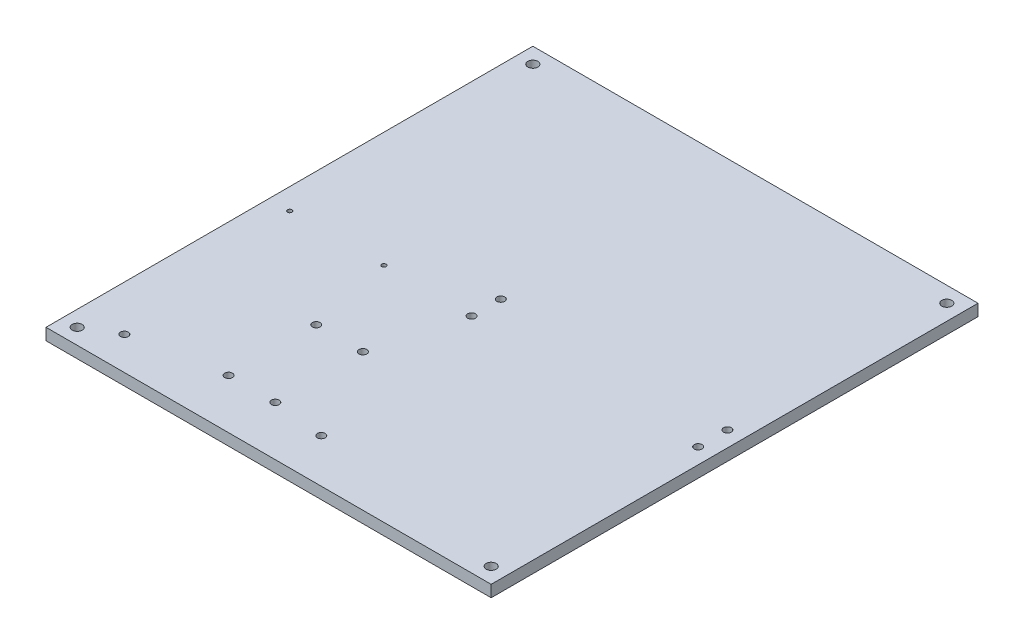
SolidWorks part; units mm, degrees
ref_plane "Front" through (0, 0, 0) normal (0, 0, 1) x (1, 0, 0)
ref_plane "Top" through (0, 0, 0) normal (0, 1, 0) x (1, 0, 0)
ref_plane "Right" through (0, 0, 0) normal (1, 0, 0) x (0, 0, -1)
sketch "Sketch1" plane through (0, 0, 0) normal (0, 1, 0) x (1, 0, 0)
  line L0 (-114.3, 125) -> (114.3, -125) construction
  line L1 (-114.3, 125) -> (114.3, 125)
  line L2 (-114.3, 125) -> (-114.3, -125)
  line L3 (-114.3, -125) -> (114.3, -125)
  line L4 (114.3, 125) -> (114.3, -125)
  dimension "D1" = 228.6
  dimension "D2" = 250
extrude "PLATE" add sketch "Sketch1" along normal mid plane 6
sketch "Sketch2" plane through (0, 3, 0) normal (0, 1, 0) x (1, 0, 0)
  line L0 (-114.3, -125) -> (114.3, -125) construction
  line L1 (114.3, -125) -> (114.3, 125) construction
  circle A0 centre (106.3, -10.7) radius 2
  circle A1 centre (106.3, 4.3) radius 2
  dimension "D1" = 114.3
  dimension "D2" = 8
  dimension "D3" = 4
  dimension "D4" = 15
extrude "MUX_BRACKET_HOLES" cut sketch "Sketch2" against normal blind 6
pattern_linear "MUX_BRACKET_PATTERN" count 2 spacing 116.35 along (-1, 0, 0) of "MUX_BRACKET_HOLES"
sketch "Sketch3" plane through (0, 3, 0) normal (0, 1, 0) x (1, 0, 0)
  circle A0 centre (-22.05, -54.5) radius 2
  circle A2 centre (-10.05, -10.7) radius 2 construction
  dimension "D1" = 10
  dimension "D2" = 4
  dimension "D3" = 43.8
extrude "PUMP_STAND_HOLE" cut sketch "Sketch3" against normal through all
pattern_linear "PUMP_STAND_PATTERN" count 2 spacing 24 along (-1, 0, 0) count 2 spacing 45 along (0, 0, 1) of "PUMP_STAND_HOLE"
sketch "Sketch4" plane through (0, 3, 0) normal (0, 1, 0) x (1, 0, 0)
  circle A0 centre (4.55, -102.5) radius 2
  circle A2 centre (-22.05, -99.5) radius 2 construction
  dimension "D1" = 26.6
  dimension "D2" = 3
  dimension "D3" = 4
extrude "PUMP_INPUT_STAND_HOLE" cut sketch "Sketch4" against normal through all
sketch "Sketch5" plane through (0, 3, 0) normal (0, 1, 0) x (1, 0, 0)
  circle A2 centre (-91.05, -108) radius 2
  circle A3 centre (-46.05, -99.5) radius 2 construction
  point P5 (-46.05, -99.5)
  dimension "D2" = 45
  dimension "D1" = 8.5
  dimension "D3" = 4
extrude "CROSS_FITTING_STAND_HOLE" cut sketch "Sketch5" against normal through all
sketch "Sketch6" plane through (0, 3, 0) normal (0, 1, 0) x (1, 0, 0)
  line L0 (-114.3, -125) -> (114.3, -125) construction
  line L1 (-114.3, 125) -> (-114.3, -125) construction
  line L2 (114.3, -125) -> (114.3, 125) construction
  line L3 (114.3, 125) -> (-114.3, 125) construction
  circle A0 centre (-106.3, -117) radius 2.58
  circle A1 centre (106.3, -117) radius 2.58
  circle A2 centre (106.3, 117) radius 2.58
  circle A3 centre (-106.3, 117) radius 2.58
  dimension "D1" = 5.16
  dimension "D2" = 8
  dimension "D3" = 8
  dimension "D4" = 8
  dimension "D5" = 8
extrude "STANDOFF_HOLES" cut sketch "Sketch6" against normal through all
sketch "Sketch7" plane through (0, 3, 0) normal (0, 1, 0) x (1, 0, 0)
  circle A0 centre (-103.45, -10.7) radius 1.1303
  circle A1 centre (-55.05, -10.7) radius 1.1303
  circle A2 centre (-10.05, -10.7) radius 2 construction
  dimension "D1" = 48.4
  dimension "D2" = 45
  dimension "D3" = 0
  dimension "D4" = 2.2606
extrude "ARDUINO_HOLES" cut sketch "Sketch7" against normal blind 10
equation "\"D4@Sketch6\"=\"D3@Sketch6\""
equation "\"D5@Sketch6\"=\"D2@Sketch6\""
